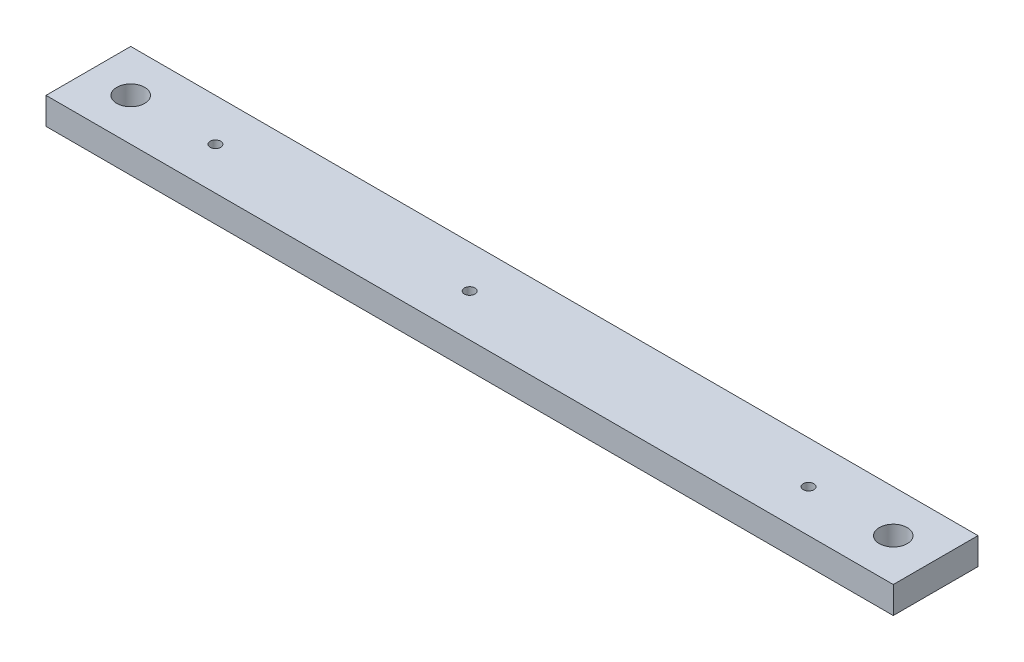
SolidWorks part; units mm, degrees
ref_plane "Front Plane" through (0, 0, 0) normal (0, 0, 1) x (1, 0, 0)
ref_plane "Top Plane" through (0, 0, 0) normal (0, 1, 0) x (1, 0, 0)
ref_plane "Right Plane" through (0, 0, 0) normal (1, 0, 0) x (0, 0, -1)
sketch "Sketch1" plane through (0, 0, 0) normal (0, 1, 0) x (1, 0, 0)
  line L0 (100, 41.428) -> (100, -20.4293) construction
  line L1 (0, 0) -> (200, 0)
  line L2 (0, 0) -> (0, 20)
  line L3 (0, 20) -> (200, 20)
  line L4 (200, 0) -> (200, 20)
  point P7 (100, 20)
  dimension "D1" = 20
  dimension "D2" = 200
extrude "Boss-Extrude1" add sketch "Sketch1" along normal blind 6.35
sketch "Sketch6" plane through (0, 6.35, 0) normal (0, 1, 0) x (1, 0, 0)
  line L0 (100, 47.5462) -> (100, -37.3799) construction
  line L1 (200, 20) -> (0, 20) construction
  point P4 (100, 20)
hole_wizard "M3x0.5 Tapped Hole1" positions "Sketch4" profile "Sketch5" tap size "M3x0.5" standard "ANSI Metric" end condition through all
sketch "Sketch4" plane through (0, 6.35, 0) normal (0, 1, 0) x (1, 0, 0)
  line L0 (0, 20) -> (0, 0) construction
  line L1 (200, 0) -> (200, 20) construction
  line L2 (100, 47.5462) -> (100, -37.3799) construction
  point P0 (30, 10)
  point P2 (170, 10)
  point P10 (0, 10)
  point P11 (200, 10)
  point P15 (90, 10)
  dimension "D1" = 70
  dimension "D2" = 70
  dimension "D3" = 60
sketch "Sketch5" plane through (30, 6.35, -10) normal (1, 0, 0) x (0, 0, 1)
  line L0 (0, 0) -> (0, 6.35)
  line L1 (0, 6.35) -> (1.25, 6.35)
  line L2 (1.25, 6.35) -> (1.25, 0)
  line L5 (1.25, 0) -> (0, 0)
  line L11 (0, -6.35) -> (0, 107.95) construction
  dimension "Thru Tap Drill Dia." = 2.5
  dimension "Thru Tap Drill Depth" = 6.35
cosmetic thread "Hole Thread1"
cosmetic thread "Hole Thread2"
cosmetic thread "Hole Thread3"
hole_wizard "M6 Clearance Hole1" positions "Sketch7" profile "Sketch8" hole size "M6" standard "ANSI Metric" end condition through all
sketch "Sketch7" plane through (0, 6.35, 0) normal (0, 1, 0) x (1, 0, 0)
  line L0 (0, 20) -> (0, 0) construction
  line L1 (200, 0) -> (200, 20) construction
  point P0 (10, 10)
  point P4 (190, 10)
  point P7 (200, 10)
  point P8 (0, 10)
  dimension "D1" = 10
  dimension "D2" = 10
sketch "Sketch8" plane through (10, 6.35, -10) normal (1, 0, 0) x (0, 0, 1)
  line L0 (0, 0) -> (0, 6.35)
  line L1 (0, 6.35) -> (3.3, 6.35)
  line L2 (3.3, 6.35) -> (3.3, 0)
  line L5 (3.3, 0) -> (0, 0)
  line L11 (0, -6.35) -> (0, 107.95) construction
  dimension "Thru Hole Dia." = 6.6
  dimension "Thru Hole Depth" = 6.35
